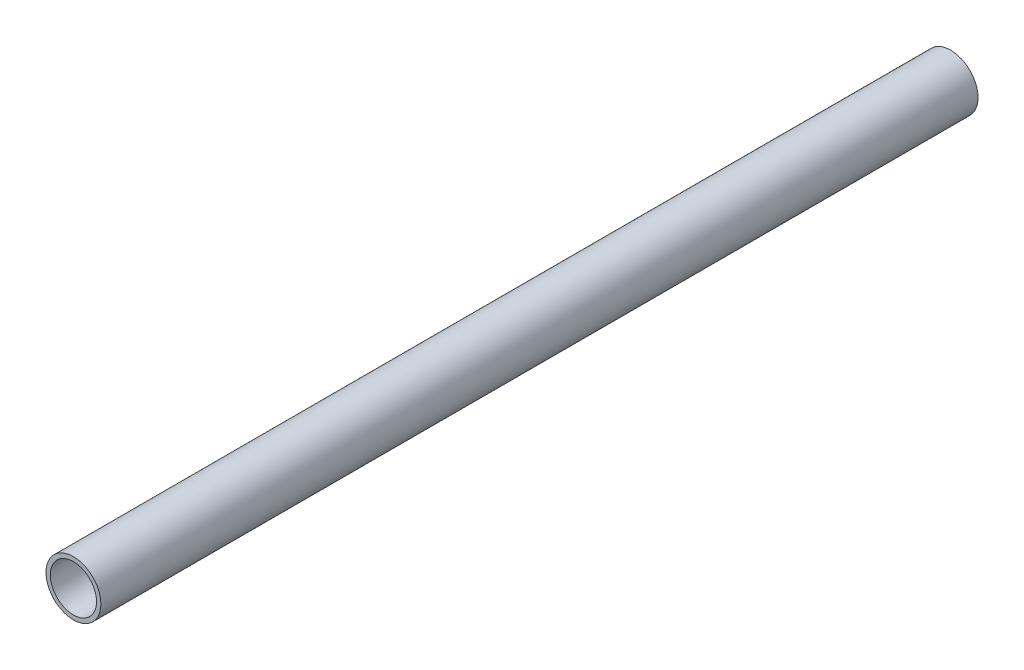
SolidWorks part; units mm, degrees
ref_plane "Front Plane" through (0, 0, 0) normal (0, 0, 1) x (1, 0, 0)
ref_plane "Top Plane" through (0, 0, 0) normal (0, 1, 0) x (1, 0, 0)
ref_plane "Right Plane" through (0, 0, 0) normal (1, 0, 0) x (0, 0, -1)
sketch "Sketch1" plane through (0, 0, 0) normal (0, 0, 1) x (1, 0, 0)
  circle A0 centre (0, 0) radius 4.7625
  dimension "D1" = 9.525
extrude "Boss-Extrude1" add sketch "Sketch1" along normal blind 152.4
sketch "Sketch2" plane through (0, 0, 152.4) normal (0, 0, 1) x (1, 0, 0)
  circle A0 centre (0, 0) radius 4.0132
  circle A1 centre (0, 0) radius 4.7625 construction
  dimension "D1" = 8.0264
extrude "Cut-Extrude1" cut sketch "Sketch2" against normal blind 25.4
